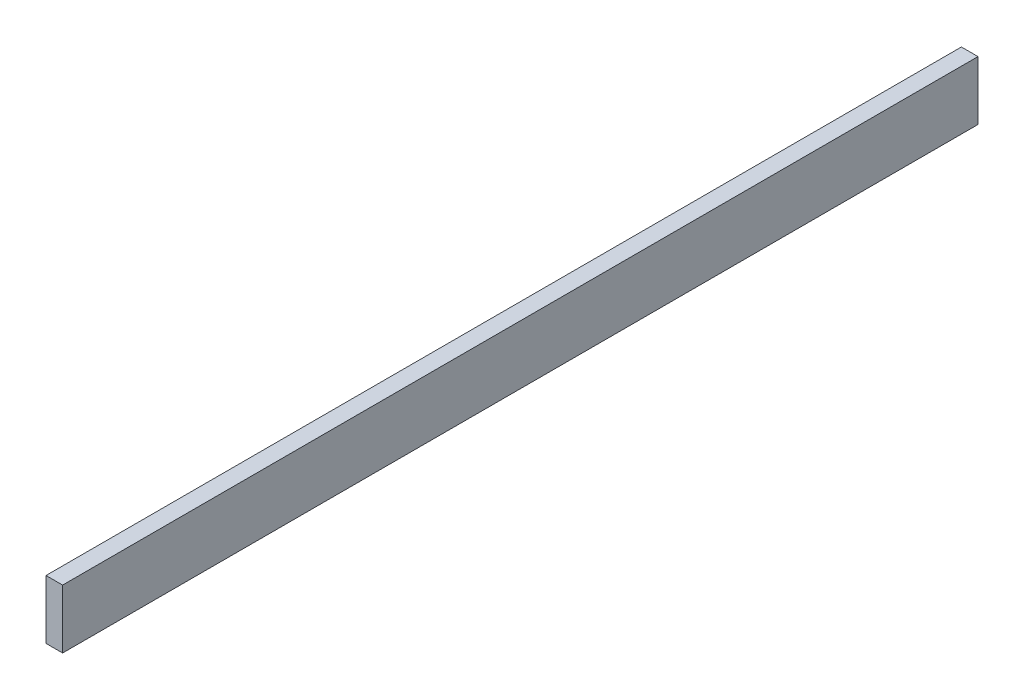
SolidWorks part; units mm, degrees
ref_plane "Front Plane" through (0, 0, 0) normal (0, 0, 1) x (1, 0, 0)
ref_plane "Top Plane" through (0, 0, 0) normal (0, 1, 0) x (1, 0, 0)
ref_plane "Right Plane" through (0, 0, 0) normal (1, 0, 0) x (0, 0, -1)
other "Configuration Table"
sketch "Sketch1" plane through (0, 0, 0) normal (0, 0, 1) x (1, 0, 0)
  line L1 (1325.3, 1527) -> (1338, 1527)
  line L2 (1325.3, 1527) -> (1325.3, 1572)
  line L3 (1325.3, 1572) -> (1338, 1572)
  line L4 (1338, 1527) -> (1338, 1572)
extrude "DET_PASIF_RAY_govde_45x12.7_1" add sketch "Sketch1" against normal blind 700 separate body
